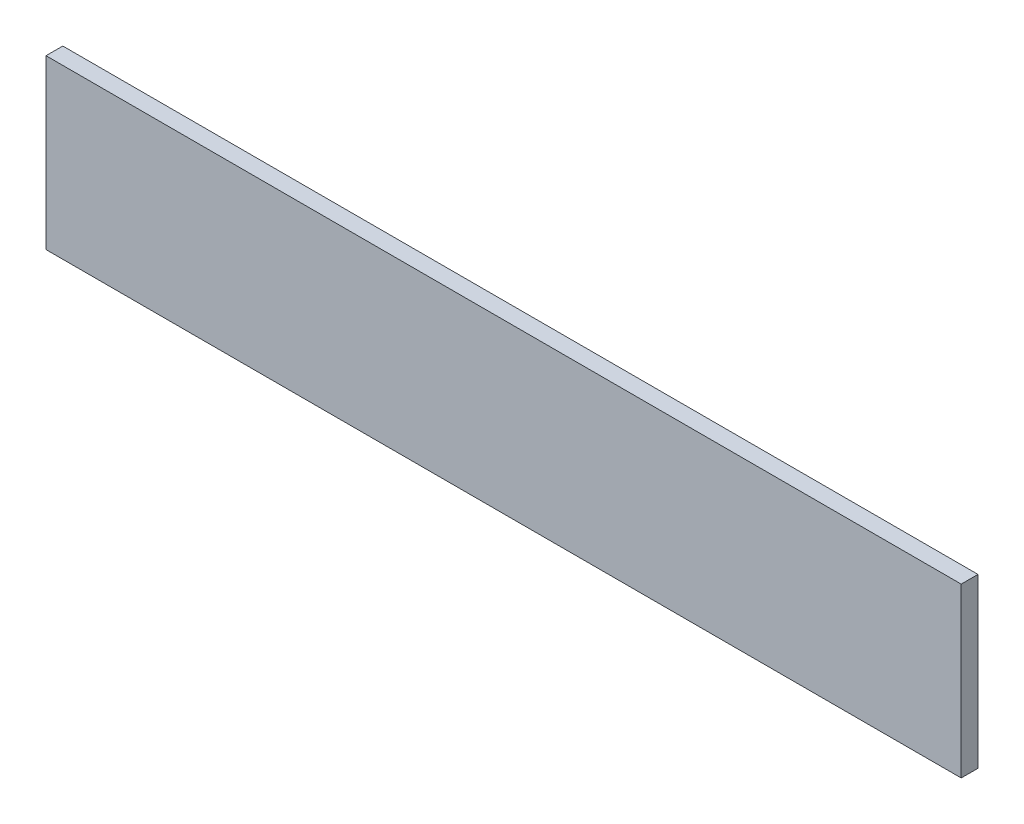
SolidWorks part; units mm, degrees
ref_plane "前视基准面" through (0, 0, 0) normal (0, 0, 1) x (1, 0, 0)
ref_plane "上视基准面" through (0, 0, 0) normal (0, 1, 0) x (1, 0, 0)
ref_plane "右视基准面" through (0, 0, 0) normal (1, 0, 0) x (0, 0, -1)
sketch "草图1" plane through (0, 0, 0) normal (0, 0, 1) x (1, 0, 0)
  line L1 (0, 0) -> (109, 0)
  line L2 (0, 0) -> (0, -20)
  line L3 (0, -20) -> (109, -20)
  line L4 (109, 0) -> (109, -20)
  dimension "D1" = 109
  dimension "D2" = 20
extrude "凸台-拉伸1" add sketch "草图1" along normal blind 2
